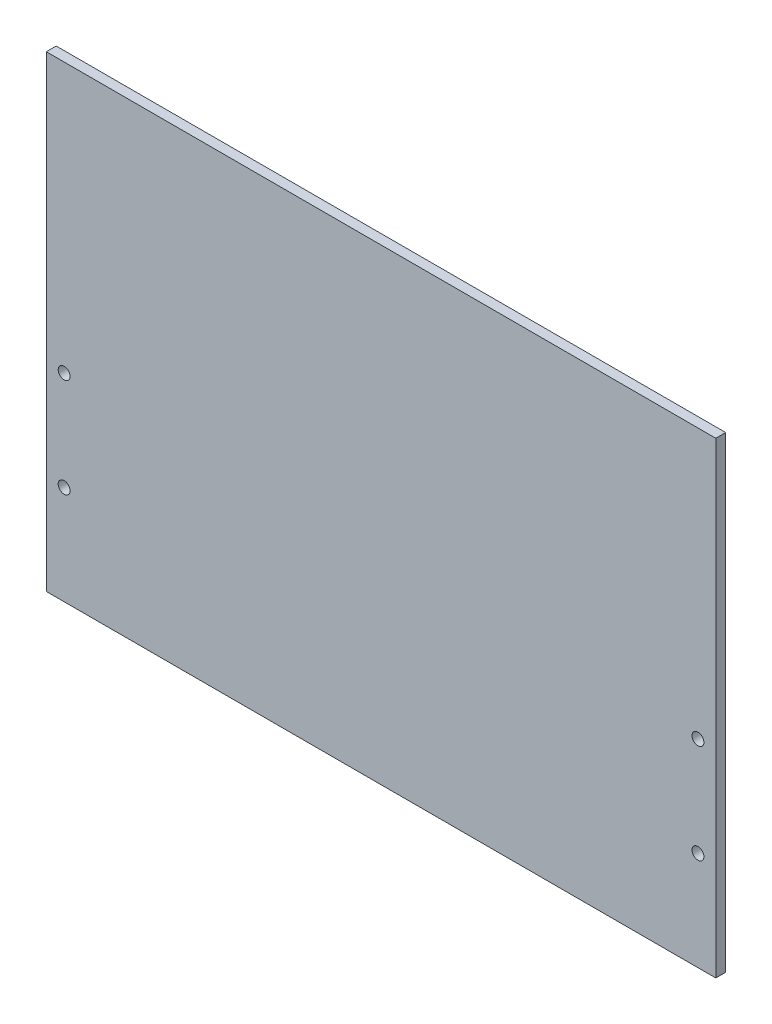
SolidWorks part; units mm, degrees
ref_plane "Front Plane" through (0, 0, 0) normal (0, 0, 1) x (1, 0, 0)
ref_plane "Top Plane" through (0, 0, 0) normal (0, 1, 0) x (1, 0, 0)
ref_plane "Right Plane" through (0, 0, 0) normal (1, 0, 0) x (0, 0, -1)
sketch "Sketch1" plane through (0, 0, 0) normal (0, 0, 1) x (1, 0, 0)
  line L0 (0, 118) -> (0, -118) construction
  line L1 (-169, -118) -> (169, -118)
  line L2 (-169, -118) -> (-169, 118)
  line L3 (-169, 118) -> (169, 118)
  line L4 (169, -118) -> (169, 118)
  line L5 (-169, -118) -> (169, 118) construction
  line L6 (-169, 118) -> (169, -118) construction
  circle A0 centre (-160, -68) radius 3
  circle A1 centre (-160, -18) radius 3
  circle A4 centre (160, -18) radius 3
  circle A5 centre (160, -68) radius 3
  point P0 (0, 0)
  dimension "D6" = 6
  dimension "D1" = 338
  dimension "D2" = 236
  dimension "D3" = 50
  dimension "D4" = 50
  dimension "D5" = 9
  dimension "D7" = 50
  dimension "D8" = 50
  dimension "D9" = 9
extrude "Boss-Extrude1" add sketch "Sketch1" along normal blind 5
